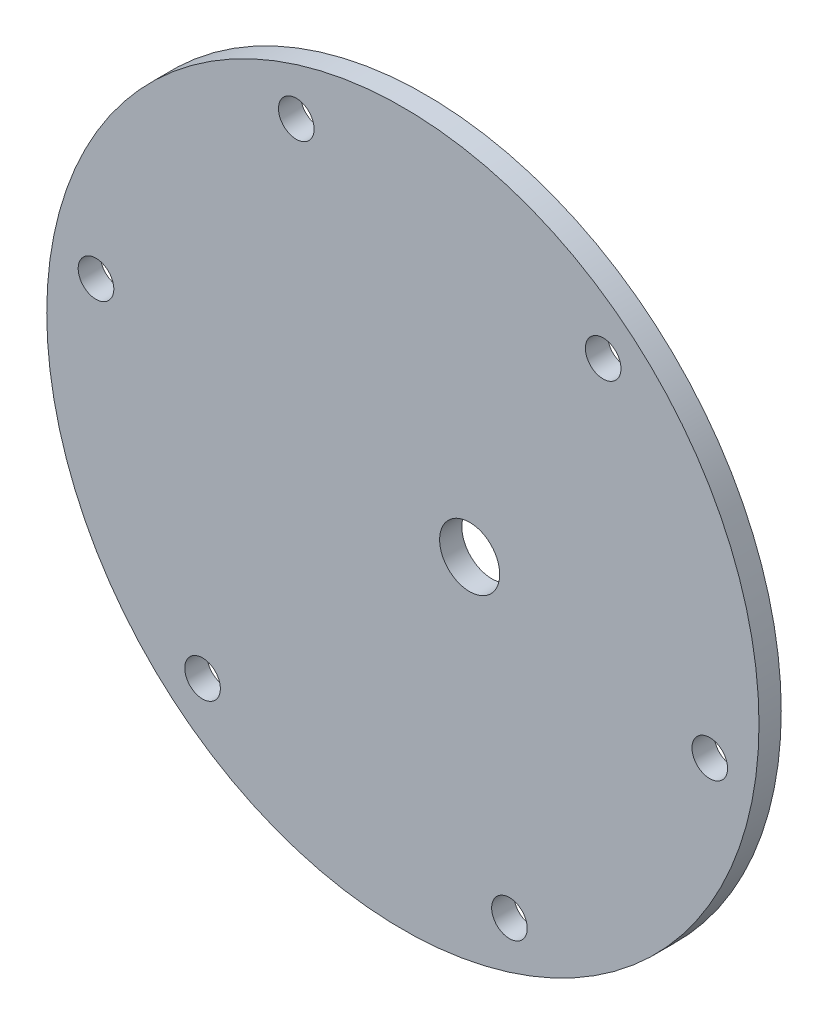
SolidWorks part; units mm, degrees
material "6063-T6"
ref_plane "Plano frontal" through (0, 0, 0) normal (0, 0, 1) x (1, 0, 0)
ref_plane "Plano superior" through (0, 0, 0) normal (0, 1, 0) x (1, 0, 0)
ref_plane "Plano direito" through (0, 0, 0) normal (1, 0, 0) x (0, 0, -1)
sketch "Esboço1" plane through (0, 0, 0) normal (0, 0, 1) x (1, 0, 0)
  circle A1 centre (0, 0) radius 80
  dimension "D2" = 160
extrude "Ressalto-extrusão1" add sketch "Esboço1" along normal blind 5
sketch "Esboço3" plane through (0, 0, 0) normal (0, 0, -1) x (-1, 0, 0)
  circle A0 centre (-15, 0) radius 6.75
  point P9 (0, 0)
  dimension "D1" = 13.5
  dimension "D3" = 15
extrude "Corte-extrusão1" cut sketch "Esboço3" against normal through all both and the other way through all
sketch "Esboço5" plane through (0, 0, 0) normal (0, 0, -1) x (-1, 0, 0)
  line L0 (0, 0) -> (0, 75.2984) construction
  line L1 (0, 0) -> (27.3265, 75.079) construction
  circle A0 centre (23.9414, 65.7785) radius 4
  circle A1 centre (68.9365, 12.1554) radius 4
  circle A2 centre (44.9951, -53.6231) radius 4
  circle A3 centre (-23.9414, -65.7785) radius 4
  circle A4 centre (-68.9365, -12.1554) radius 4
  circle A5 centre (-44.9951, 53.6231) radius 4
  point P19 (0, 0)
  dimension "D2" = 8
  dimension "D1" = 20
  dimension "D3" = 70
  dimension "D4" = 6
extrude "Corte-extrusão2" cut sketch "Esboço5" against normal through all both and the other way through all
